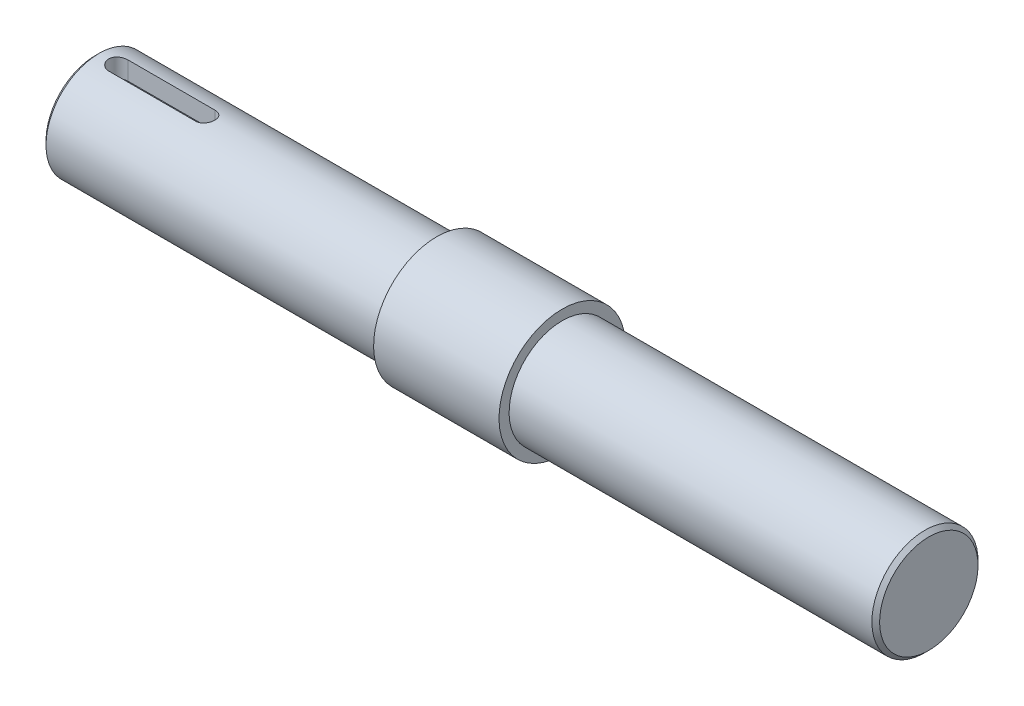
SolidWorks part; units mm, degrees
ref_plane "Alzado" through (0, 0, 0) normal (0, 0, 1) x (1, 0, 0)
ref_plane "Planta" through (0, 0, 0) normal (0, 1, 0) x (1, 0, 0)
ref_plane "Vista lateral" through (0, 0, 0) normal (1, 0, 0) x (0, 0, -1)
sketch "Croquis1" plane through (0, 0, 0) normal (0, 0, 1) x (1, 0, 0)
  line L0 (0, 0) -> (0, 27.5)
  line L2 (177, 27.5) -> (177, 32.725)
  line L3 (177, 32.725) -> (242, 32.725)
  line L4 (242, 32.725) -> (242, 27.5)
  line L8 (432, 27.5) -> (432, 0)
  line L9 (432, 0) -> (0, 0)
  line L10 (242, 27.5) -> (432, 27.5)
  line L12 (0, 27.5) -> (177, 27.5)
  dimension "D1" = 177
  dimension "D2" = 32.725
  dimension "D3" = 27.5
  dimension "D4" = 432
  dimension "D6" = 65
revolve "Revolución1" add sketch "Croquis1" angle 360 about L9
chamfer "Chaflán1" distance 2 angle 45 2 edges at (432, 27.5, 0) (0, 27.5, 0)
ref_plane "Plano1" through (0, 27.5, 0) normal (0, 1, 0) x (1, 0, 0)
sketch "Croquis2" plane through (0, 27.5, 0) normal (0, 1, 0) x (1, 0, 0)
  line L0 (57, 5) -> (12, 5)
  line L1 (57, 0) -> (12, 0)
  line L2 (57, -5) -> (12, -5)
  line L3 (12, 0) -> (2, 0)
  line L4 (2, 27.5) -> (2, -27.5) construction
  arc A0 (57, 5) -> (57, -5) centre (57, 0) cw
  arc A1 (12, 5) -> (12, -5) centre (12, 0) ccw
  dimension "D1" = 5
  dimension "D2" = 5
extrude "Cortar-Extruir1" cut sketch "Croquis2" against normal blind 10
